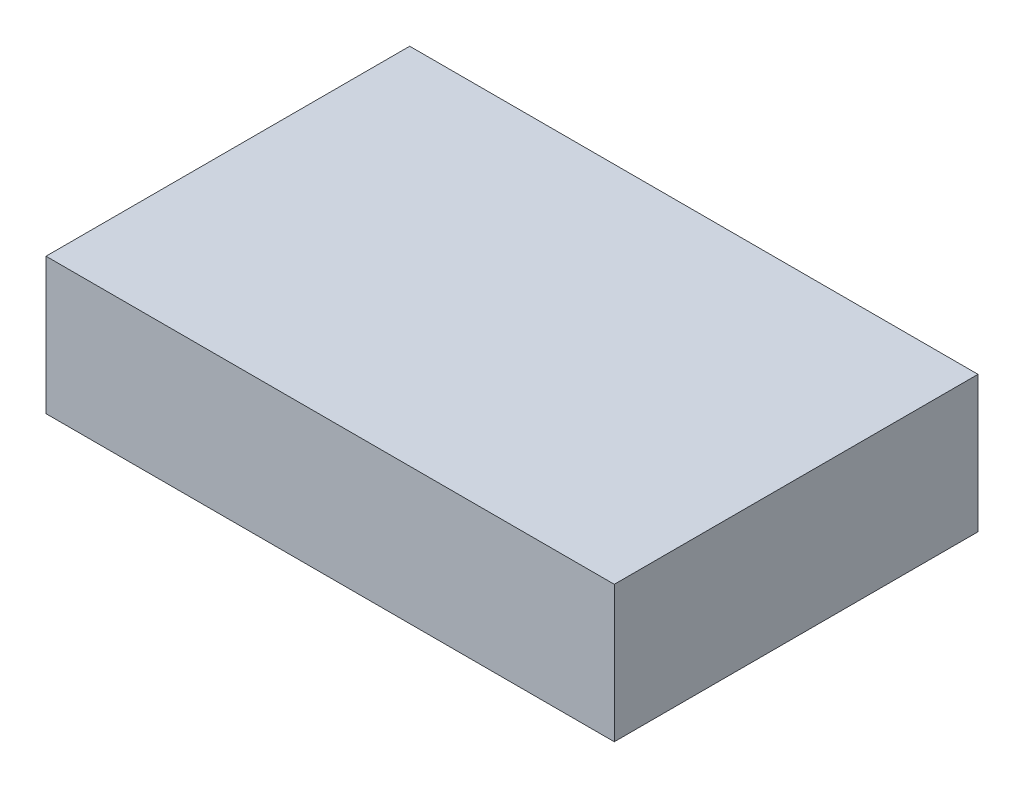
SolidWorks part; units mm, degrees
ref_plane "Płaszczyzna przednia" through (0, 0, 0) normal (0, 0, 1) x (1, 0, 0)
ref_plane "Płaszczyzna górna" through (0, 0, 0) normal (0, 1, 0) x (1, 0, 0)
ref_plane "Płaszczyzna prawa" through (0, 0, 0) normal (1, 0, 0) x (0, 0, -1)
sketch "Szkic1" plane through (0, 0, 0) normal (0, 1, 0) x (1, 0, 0)
  line L1 (-62.5, 40) -> (62.5, 40)
  line L2 (-62.5, 40) -> (-62.5, -40)
  line L3 (-62.5, -40) -> (62.5, -40)
  line L4 (62.5, 40) -> (62.5, -40)
  line L5 (-62.5, 40) -> (62.5, -40) construction
  line L6 (-62.5, -40) -> (62.5, 40) construction
  point P0 (0, 0)
  point P6 (0, 0)
  point P7 (0, 0)
  dimension "D1" = 125
  dimension "D2" = 80
extrude "Dodanie-wyciągnięcie1" add sketch "Szkic1" against normal blind 30
shell "Skorupa2" thickness 3
sketch "Szkic3" plane through (-62.5, 0, 0) normal (-1, 0, 0) x (0, 0, 1)
  line L1 (-29.771, -8.548) -> (-17.6045, -8.548)
  line L2 (-29.771, -8.548) -> (-29.771, -13.8938)
  line L3 (-29.771, -13.8938) -> (-17.6045, -13.8938)
  line L4 (-17.6045, -8.548) -> (-17.6045, -13.8938)
  line L5 (-29.771, -8.548) -> (-17.6045, -13.8938) construction
  line L6 (-29.771, -13.8938) -> (-17.6045, -8.548) construction
  point P0 (-23.6878, -11.2209)
